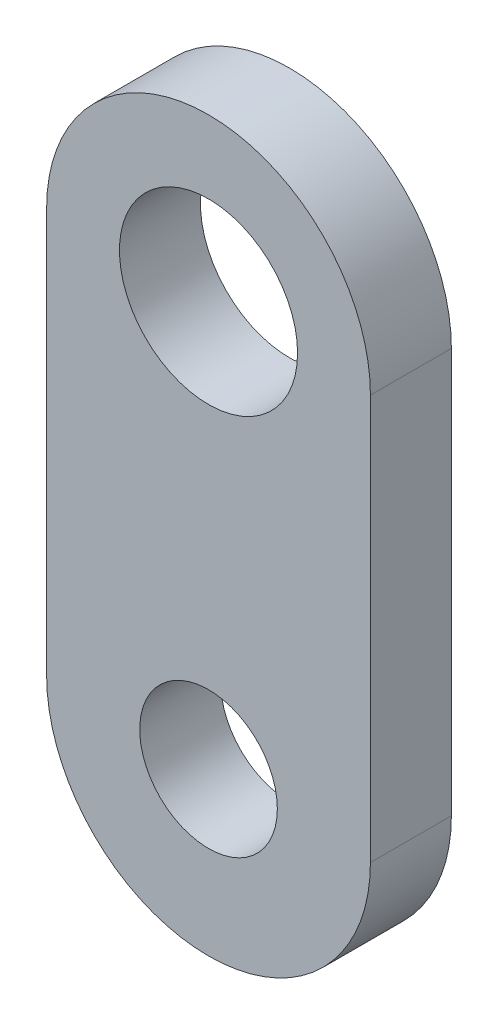
SolidWorks part; units mm, degrees
ref_plane "Front Plane" through (0, 0, 0) normal (0, 0, 1) x (1, 0, 0)
ref_plane "Top Plane" through (0, 0, 0) normal (0, 1, 0) x (1, 0, 0)
ref_plane "Right Plane" through (0, 0, 0) normal (1, 0, 0) x (0, 0, -1)
sketch "Sketch1" plane through (0, 0, 0) normal (0, 0, 1) x (1, 0, 0)
  line L2 (20, 25) -> (20, -25)
  line L4 (-20, 25) -> (-20, -25)
  line L5 (20, 25) -> (-20, -25) construction
  line L6 (20, -25) -> (-20, 25) construction
  arc A0 (-20, -25) -> (20, -25) centre (0, -25) ccw
  arc A1 (-20, 25) -> (20, 25) centre (0, 25) cw
  circle A2 centre (0, 25) radius 11
  circle A3 centre (0, -25) radius 8.5
  point P0 (0, 0)
  dimension "D3" = 22
  dimension "D4" = 17
  dimension "D5" = 20
  dimension "D1" = 40
  dimension "D2" = 50
extrude "Boss-Extrude1" add sketch "Sketch1" along normal blind 10
